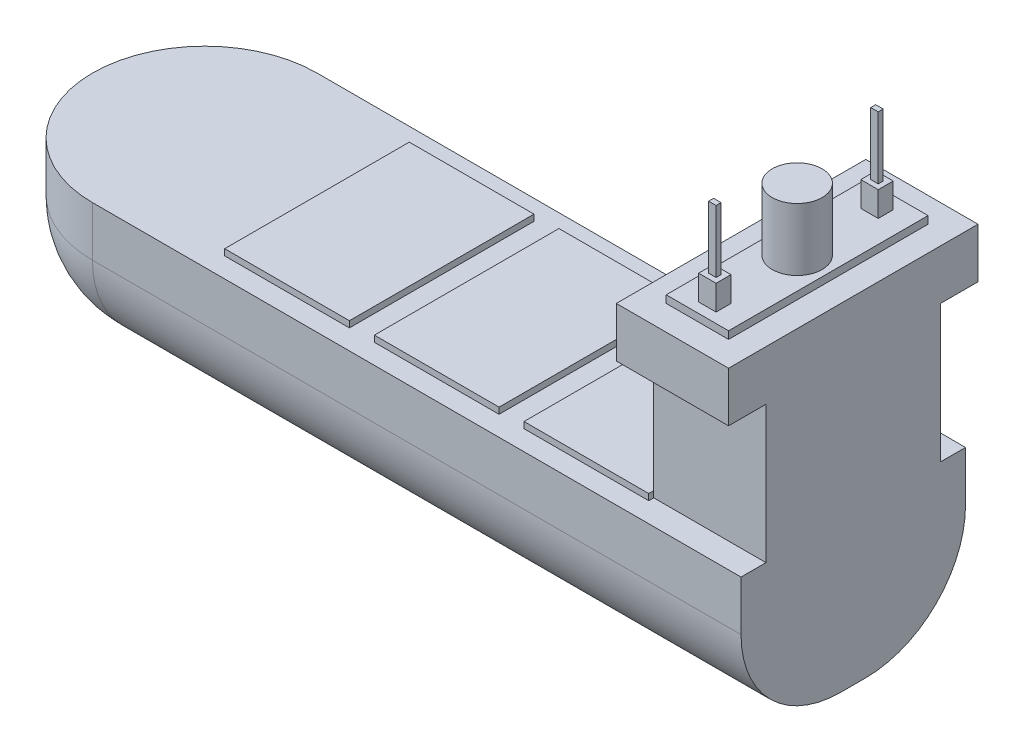
SolidWorks part; units mm, degrees
ref_plane "Alzado" through (0, 0, 0) normal (0, 0, 1) x (1, 0, 0)
ref_plane "Planta" through (0, 0, 0) normal (0, 1, 0) x (1, 0, 0)
ref_plane "Vista lateral" through (0, 0, 0) normal (1, 0, 0) x (0, 0, -1)
sketch "Croquis2" plane through (0, 0, 0) normal (0, 1, 0) x (1, 0, 0)
  line L1 (130, -45) -> (-130, -45)
  line L2 (130, -45) -> (130, 45)
  line L3 (130, 45) -> (-130, 45)
  arc A0 (-130, 45) -> (-130, -45) centre (-130, 0) ccw
  point P0 (0, 0)
  dimension "D1" = 90
  dimension "260" = 260
extrude "Saliente-Extruir1" add sketch "Croquis2" along normal blind 60
fillet "Redondeo2" radius 40 3 edges at (0, 0, -45) (-175, 0, 0) (0, 0, 45)
sketch "Croquis3" plane through (0, 60, 0) normal (0, 1, 0) x (1, 0, 0)
  line L1 (85, 35) -> (130, 35)
  line L2 (85, 35) -> (85, -35)
  line L3 (85, -35) -> (130, -35)
  line L4 (130, 35) -> (130, -35)
  line L5 (85, 35) -> (130, -35) construction
  line L6 (85, -35) -> (130, 35) construction
  line L7 (-130, -45) -> (130, -45) construction
  line L9 (130, 45) -> (-130, 45) construction
  line L10 (130, -45) -> (130, 45) construction
  arc A0 (-130, 45) -> (-130, -45) centre (-130, 0) ccw construction
  point P0 (107.5, 0)
  dimension "D1" = 215
  dimension "D2" = 10
  dimension "D3" = 10
extrude "Saliente-Extruir2" add sketch "Croquis3" along normal blind 75
sketch "Croquis6" plane through (0, 0, -35) normal (0, 0, -1) x (-1, 0, 0)
  line L0 (-85, 135) -> (-85, 60) construction
  line L1 (-130, 135) -> (-85, 135)
  line L2 (-130, 135) -> (-130, 115)
  line L3 (-130, 115) -> (-85, 115)
  line L4 (-85, 135) -> (-85, 115)
  dimension "D1" = 20
extrude "Saliente-Extruir5" add sketch "Croquis6" along normal blind 15
sketch "Croquis7" plane through (0, 0, 35) normal (0, 0, 1) x (1, 0, 0)
  line L1 (85, 135) -> (130, 135)
  line L2 (85, 135) -> (85, 115)
  line L3 (85, 115) -> (130, 115)
  line L4 (130, 135) -> (130, 115)
extrude "Saliente-Extruir6" add sketch "Croquis7" along normal blind 15
sketch "Croquis8" plane through (0, 60, 0) normal (0, 1, 0) x (1, 0, 0)
  line L0 (-130, -45) -> (130, -45) construction
  line L1 (-25, 37) -> (25, 37)
  line L2 (-25, 37) -> (-25, -37)
  line L3 (-25, -37) -> (25, -37)
  line L4 (25, 37) -> (25, -37)
  line L5 (-25, 37) -> (25, -37) construction
  line L6 (-25, -37) -> (25, 37) construction
  line L7 (85, 35) -> (85, -35) construction
  line L9 (-85, 37) -> (-35, 37)
  line L10 (-85, 37) -> (-85, -37)
  line L11 (-85, -37) -> (-35, -37)
  line L12 (-35, 37) -> (-35, -37)
  line L13 (35, 37) -> (85, 37)
  line L14 (35, 37) -> (35, -37)
  line L15 (35, -37) -> (85, -37)
  line L16 (85, 37) -> (85, -37)
  point P0 (0, 0)
  dimension "D1" = 8
  dimension "D2" = 60
  dimension "D3" = 10
  dimension "D4" = 10
extrude "Saliente-Extruir7" add sketch "Croquis8" along normal blind 2.5
sketch "Croquis9" plane through (0, 135, 0) normal (0, 1, 0) x (1, 0, 0)
  line L0 (130, -50) -> (130, 50) construction
  line L1 (95, 40) -> (120, 40)
  line L2 (95, 40) -> (95, -40)
  line L3 (95, -40) -> (120, -40)
  line L4 (120, 40) -> (120, -40)
  line L5 (85, 35) -> (85, -35) construction
  line L6 (130, -50) -> (85, -50) construction
  point P10 (107.5, -50)
  dimension "D1" = 10
  dimension "D2" = 10
  dimension "D3" = 10
  dimension "D4" = 10
extrude "Saliente-Extruir8" add sketch "Croquis9" along normal blind 3
sketch "Croquis10" plane through (0, 138, 0) normal (0, 1, 0) x (1, 0, 0)
  line L0 (95, -40) -> (120, -40) construction
  line L1 (104, -30) -> (111, -30)
  line L2 (104, -30) -> (104, -36)
  line L3 (104, -36) -> (111, -36)
  line L4 (111, -30) -> (111, -36)
  line L5 (120, -40) -> (120, 40) construction
  line L6 (95, 40) -> (95, -40) construction
  line L7 (120, 40) -> (95, 40) construction
  line L8 (0, 0) -> (50000, 0) construction
  point P6 (107.5, -36)
  point P13 (107.5, 40)
  dimension "D1" = 4
  dimension "D2" = 9
  dimension "D3" = 9
  dimension "D4" = 70
extrude "Saliente-Extruir9" add sketch "Croquis10" along normal blind 10
sketch "Croquis12" plane through (0, 148, 0) normal (0, 1, 0) x (1, 0, 0)
  line L0 (111, -30) -> (104, -30) construction
  line L1 (106, -32) -> (109, -32)
  line L2 (106, -32) -> (106, -34)
  line L3 (106, -34) -> (109, -34)
  line L4 (109, -32) -> (109, -34)
  line L5 (104, -36) -> (111, -36) construction
  line L6 (111, -36) -> (111, -30) construction
  line L8 (104, -30) -> (104, -36) construction
  dimension "D1" = 2
  dimension "D2" = 2
  dimension "D3" = 2
  dimension "D4" = 2
extrude "Saliente-Extruir10" add sketch "Croquis12" along normal blind 25
pattern_linear "MatrizL1" count 2 spacing 65 along (0, 0, -1) of "Saliente-Extruir9", "Saliente-Extruir10"
sketch "Croquis13" plane through (0, 138, 0) normal (0, 1, 0) x (1, 0, 0)
  line L0 (0, 0) -> (-50000, 0) construction
  line L5 (107.5, 40) -> (107.5, -49960) construction
  line L6 (120, 40) -> (95, 40) construction
  circle A0 centre (107.5, 0) radius 10
  point P11 (107.5, 40)
extrude "Saliente-Extruir11" add sketch "Croquis13" along normal blind 25
scale "Escala3" scale about centroid uniform scaling yes scale factor 2.5
